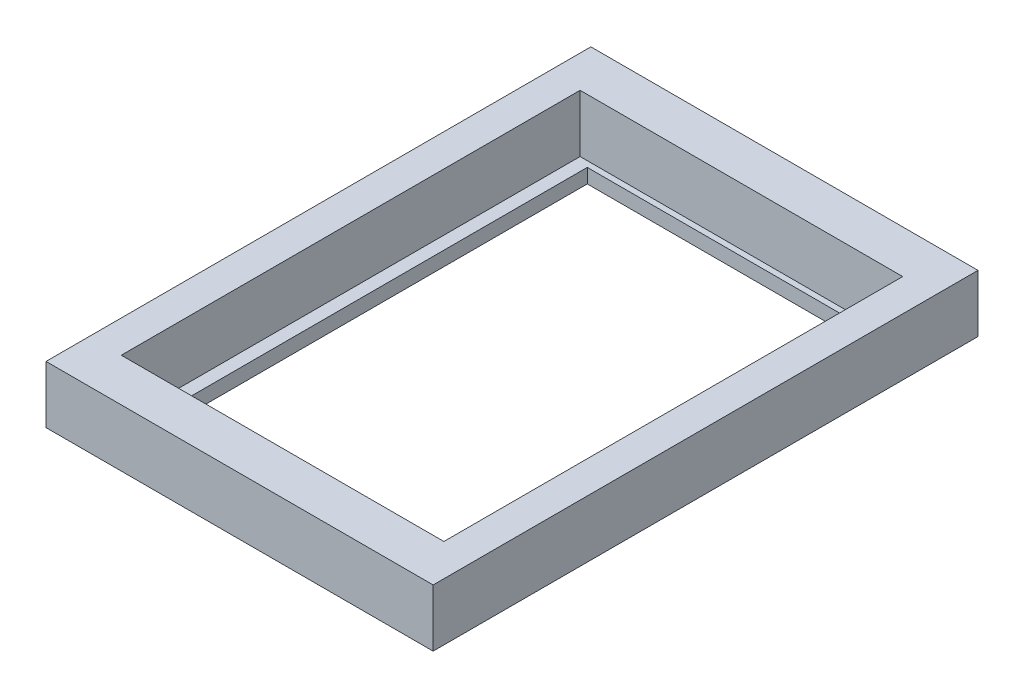
SolidWorks part; units mm, degrees
ref_plane "Front Plane" through (0, 0, 0) normal (0, 0, 1) x (1, 0, 0)
ref_plane "Top Plane" through (0, 0, 0) normal (0, 1, 0) x (1, 0, 0)
ref_plane "Right Plane" through (0, 0, 0) normal (1, 0, 0) x (0, 0, -1)
sketch "Sketch3" plane through (0, 0, 0) normal (0, 1, 0) x (1, 0, 0)
  line L1 (-54, 76) -> (54, 76)
  line L2 (-54, 76) -> (-54, -76)
  line L3 (-54, -76) -> (54, -76)
  line L4 (54, 76) -> (54, -76)
  line L5 (-54, 76) -> (54, -76) construction
  line L6 (-54, -76) -> (54, 76) construction
  point P0 (0, 0)
  dimension "D1" = 108
  dimension "D2" = 152
extrude "Boss-Extrude1" add sketch "Sketch3" along normal blind 16
ref_plane "Tabletop" through (0, 16, 0) normal (0, 1, 0) x (1, 0, 0)
sketch "Sketch5" plane through (0, 16, 0) normal (0, 1, 0) x (1, 0, 0)
  line L1 (-41.375, -62.375) -> (41.375, -62.375)
  line L2 (-41.375, -62.375) -> (-41.375, 62.375)
  line L3 (-41.375, 62.375) -> (41.375, 62.375)
  line L4 (41.375, -62.375) -> (41.375, 62.375)
  line L5 (-41.375, -62.375) -> (41.375, 62.375) construction
  line L6 (-41.375, 62.375) -> (41.375, -62.375) construction
  point P0 (0, 0)
  dimension "D1" = 82.75
  dimension "D2" = 124.75
sketch "Sketch6" plane through (0, 16, 0) normal (0, 1, 0) x (1, 0, 0)
  line L1 (-45, -64) -> (45, -64)
  line L2 (-45, -64) -> (-45, 64)
  line L3 (-45, 64) -> (45, 64)
  line L4 (45, -64) -> (45, 64)
  line L5 (-45, -64) -> (45, 64) construction
  line L6 (-45, 64) -> (45, -64) construction
  point P0 (0, 0)
  dimension "D1" = 90
  dimension "D2" = 128
sketch "Sketch7" plane through (0, 0, 0) normal (0, -1, 0) x (1, 0, 0)
  line L1 (-49, -69) -> (49, -69)
  line L2 (-49, -69) -> (-49, 69)
  line L3 (-49, 69) -> (49, 69)
  line L4 (49, -69) -> (49, 69)
  line L5 (-49, -69) -> (49, 69) construction
  line L6 (-49, 69) -> (49, -69) construction
  point P0 (0, 0)
  dimension "D1" = 98
  dimension "D2" = 138
extrude "Boss-Extrude2" add sketch "Sketch7" along normal blind 4
extrude "Cut-Extrude1" cut sketch "Sketch5" against normal through all
extrude "Cut-Extrude2" cut sketch "Sketch6" against normal blind 16
